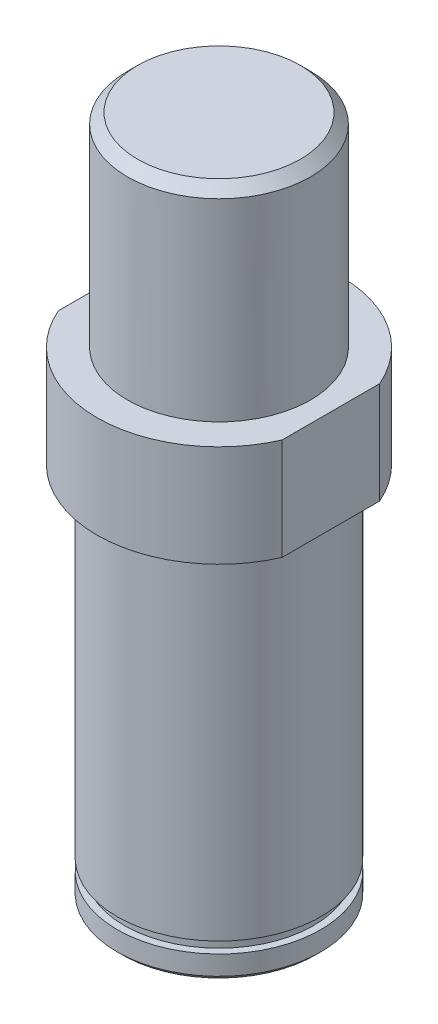
SolidWorks part; units mm, degrees
material "45"
ref_plane "前视基准面" through (0, 0, 0) normal (0, 0, 1) x (1, 0, 0)
ref_plane "上视基准面" through (0, 0, 0) normal (0, 1, 0) x (1, 0, 0)
ref_plane "右视基准面" through (0, 0, 0) normal (1, 0, 0) x (0, 0, -1)
sketch "草图1" plane through (0, 0, 0) normal (0, 0, 1) x (1, 0, 0)
  line L0 (0, 0) -> (0, 292.6233) construction
  line L1 (0, 0) -> (10, 0)
  line L2 (10, 0) -> (10, 1.9929)
  line L3 (9, 52) -> (0, 52)
  line L4 (10, 1.9929) -> (10, 22)
  line L6 (0, 0) -> (0, 52)
  line L9 (9, 32) -> (12, 32)
  line L10 (12, 32) -> (12, 22)
  line L11 (12, 22) -> (10, 22)
  line L12 (9, 32) -> (9, 52)
  dimension "D1" = 20
  dimension "D2" = 10
  dimension "D3" = 9
  dimension "D7" = 10
  dimension "D8" = 12
  dimension "D9" = 22
revolve "旋转1" add sketch "草图1" angle 360 about L0
cosmetic thread "装饰螺纹线1" parameters "D2"=15.294
chamfer "倒角1" distance 1 angle 45 1 edges at (0, 52, -9)
sketch "草图2" plane through (0, 32, 0) normal (0, 1, 0) x (1, 0, 0)
  line L0 (-11, 6.9282) -> (-11, -6.9282)
  line L1 (11, 6.9282) -> (11, -6.9282)
  circle A0 centre (0, 0) radius 13
  circle M2 centre (0, 0) radius 12
  dimension "D3" = 26
  dimension "D1" = 22
  dimension "D2" = 11
extrude "切除-拉伸1" cut sketch "草图2" against normal through all contours L0 M2 | L1 M2
sketch "草图3" plane through (0, 0, 0) normal (0, -1, 0) x (1, 0, 0)
  circle A0 centre (0, 0) radius 10
  dimension "D1" = 20
extrude "凸台-拉伸1" add sketch "草图3" along normal blind 15
chamfer "倒角2" distance 0.5 angle 45 1 edges at (0, -15, -10)
sketch "草图7" plane through (0, 0, 0) normal (1, 0, 0) x (0, 0, -1)
  line L0 (0, 52) -> (0, -14.5) construction
  line L1 (8, 52) -> (-8, 52) construction
  line L2 (10, -14.5) -> (-10, -14.5) construction
  line L3 (-9.5, -15) -> (9.5, -15) construction
  line L4 (10, -11.5) -> (9.3, -11.5)
  line L5 (10, -11.5) -> (10, -12.6)
  line L6 (10, -12.6) -> (9.3, -12.6)
  line L7 (9.3, -11.5) -> (9.3, -12.6)
  dimension "D1" = 2.4
  dimension "D2" = 9.3
  dimension "D3" = 10
  dimension "D4" = 1.1
revolve "切除-旋转1" cut sketch "草图7" angle 360 about L0
